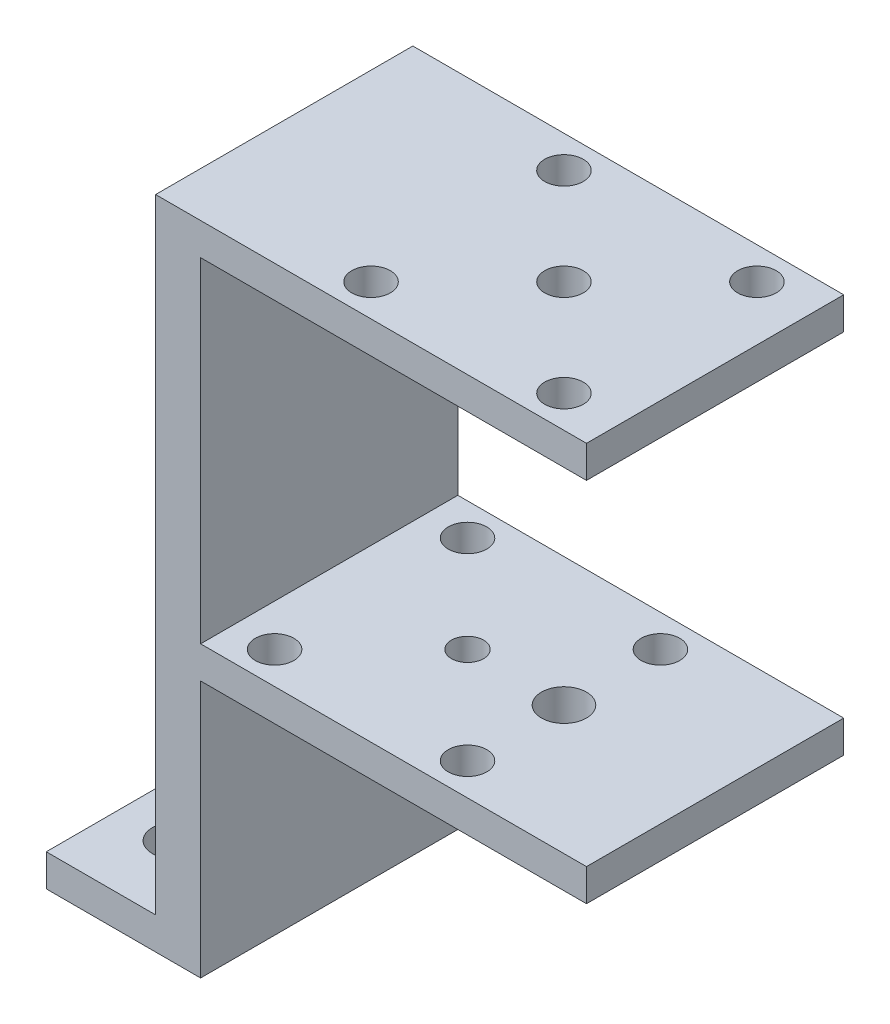
SolidWorks part; units mm, degrees
ref_plane "Alzado" through (0, 0, 0) normal (0, 0, 1) x (1, 0, 0)
ref_plane "Planta" through (0, 0, 0) normal (0, 1, 0) x (1, 0, 0)
ref_plane "Vista lateral" through (0, 0, 0) normal (1, 0, 0) x (0, 0, -1)
sketch "Croquis1" plane through (0, 0, 0) normal (0, 0, 1) x (1, 0, 0)
  line L0 (0, 0) -> (0, 40)
  line L1 (0, 40) -> (60, 40)
  line L2 (60, 40) -> (60, 45)
  line L3 (60, 45) -> (0, 45)
  line L4 (0, 45) -> (0, 97)
  line L5 (0, 97) -> (60, 97)
  line L6 (60, 97) -> (60, 102)
  line L7 (60, 102) -> (-7, 102)
  line L8 (-7, 102) -> (-7, 5)
  line L9 (-7, 5) -> (-24, 5)
  line L10 (-24, 5) -> (-24, 0)
  line L11 (-24, 0) -> (0, 0)
  dimension "D1" = 5
  dimension "D2" = 7
  dimension "D3" = 17
  dimension "D4" = 60
  dimension "D5" = 52
  dimension "D6" = 40
extrude "Saliente-Extruir1" add sketch "Croquis1" along normal blind 40
sketch "Croquis2" plane through (0, 5, 0) normal (0, 1, 0) x (1, 0, 0)
  line L0 (-15.5, 0) -> (-15.5, -40) construction
  line L1 (-7, 0) -> (-24, 0) construction
  line L2 (-7, -40) -> (-24, -40) construction
  circle A0 centre (-15.5, -11.5) radius 3.5
  circle A1 centre (-15.5, -28.5) radius 3.5
  dimension "D2" = 7
  dimension "D3" = 8
  dimension "D1" = 8
extrude "Cortar-Extruir1" cut sketch "Croquis2" against normal up to next
sketch "Croquis3" plane through (0, 102, 0) normal (0, 1, 0) x (1, 0, 0)
  line L0 (6.5, -35) -> (36.5, -35) construction
  line L1 (36.5, -35) -> (36.5, -5) construction
  line L2 (36.5, -5) -> (6.5, -5) construction
  line L3 (6.5, -5) -> (6.5, -35) construction
  line L4 (60, 0) -> (-7, 0) construction
  line L7 (-7, -40) -> (-7, 0) construction
  circle A0 centre (6.5, -5) radius 3
  circle A1 centre (36.5, -5) radius 3
  circle A2 centre (6.5, -35) radius 3
  circle A3 centre (36.5, -35) radius 3
  dimension "D1" = 6
  dimension "D2" = 30
  dimension "D3" = 30
  dimension "D4" = 5
  dimension "D5" = 13.5
extrude "Cortar-Extruir4" cut sketch "Croquis3" against normal up to next from surface
sketch "Croquis4" plane through (0, 45, 0) normal (0, 1, 0) x (1, 0, 0)
  line L0 (6.5, -5) -> (36.5, -5) construction
  line L1 (21.5, -5) -> (21.5, -35) construction
  line L3 (6.5, -35) -> (36.5, -35) construction
  circle A0 centre (21.5, -20) radius 2.5
  circle A1 centre (36.5, -20) radius 3.5
  dimension "D1" = 7
  dimension "D2" = 5
  dimension "D3" = 15
extrude "Cortar-Extruir3" cut sketch "Croquis4" against normal up to next
sketch "Croquis5" plane through (0, 102, 0) normal (0, 1, 0) x (1, 0, 0)
  line L0 (21.5, -35) -> (51.5, -35) construction
  line L1 (51.5, -35) -> (51.5, -5) construction
  line L2 (51.5, -5) -> (21.5, -5) construction
  line L3 (21.5, -5) -> (21.5, -35) construction
  line L4 (21.5, -5) -> (51.5, -35) construction
  line L5 (21.5, -35) -> (51.5, -5) construction
  circle A0 centre (21.5, -5) radius 3
  circle A1 centre (51.5, -5) radius 3
  circle A2 centre (21.5, -35) radius 3
  circle A3 centre (51.5, -35) radius 3
  circle A4 centre (36.5, -20) radius 3
  circle A5 centre (36.5, -20) radius 3.5 construction
  dimension "D1" = 6
  dimension "D2" = 30
  dimension "D3" = 30
extrude "Cortar-Extruir5" cut sketch "Croquis5" against normal up to next
